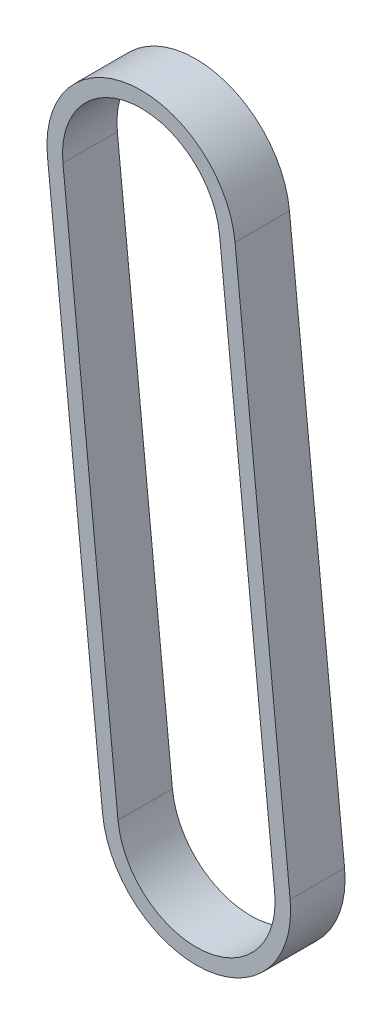
SolidWorks part; units mm, degrees
material "BUTYL"
ref_plane "前视基准面" through (0, 0, 0) normal (0, 0, 1) x (1, 0, 0)
ref_plane "上视基准面" through (0, 0, 0) normal (0, 1, 0) x (1, 0, 0)
ref_plane "右视基准面" through (0, 0, 0) normal (1, 0, 0) x (0, 0, -1)
sketch "草图2" plane through (0, 0, 0) normal (0, 0, 1) x (1, 0, 0)
  line L0 (0, 0) -> (1, 0) construction
  line L1 (0, 0) -> (0, 1) construction
  line L2 (-32.7393, -40.2046) -> (-39.8217, 29.4362)
  line L3 (-19.6756, 31.485) -> (-12.5932, -38.1558)
  arc A0 (-12.5932, -38.1558) -> (-32.7393, -40.2046) centre (-22.6663, -39.1802) cw
  arc A1 (-39.8217, 29.4362) -> (-19.6756, 31.485) centre (-29.7486, 30.4606) cw
extrude "拉伸-薄壁1" add sketch "草图2" along normal mid plane 7 thin thin type one direction wall 2
